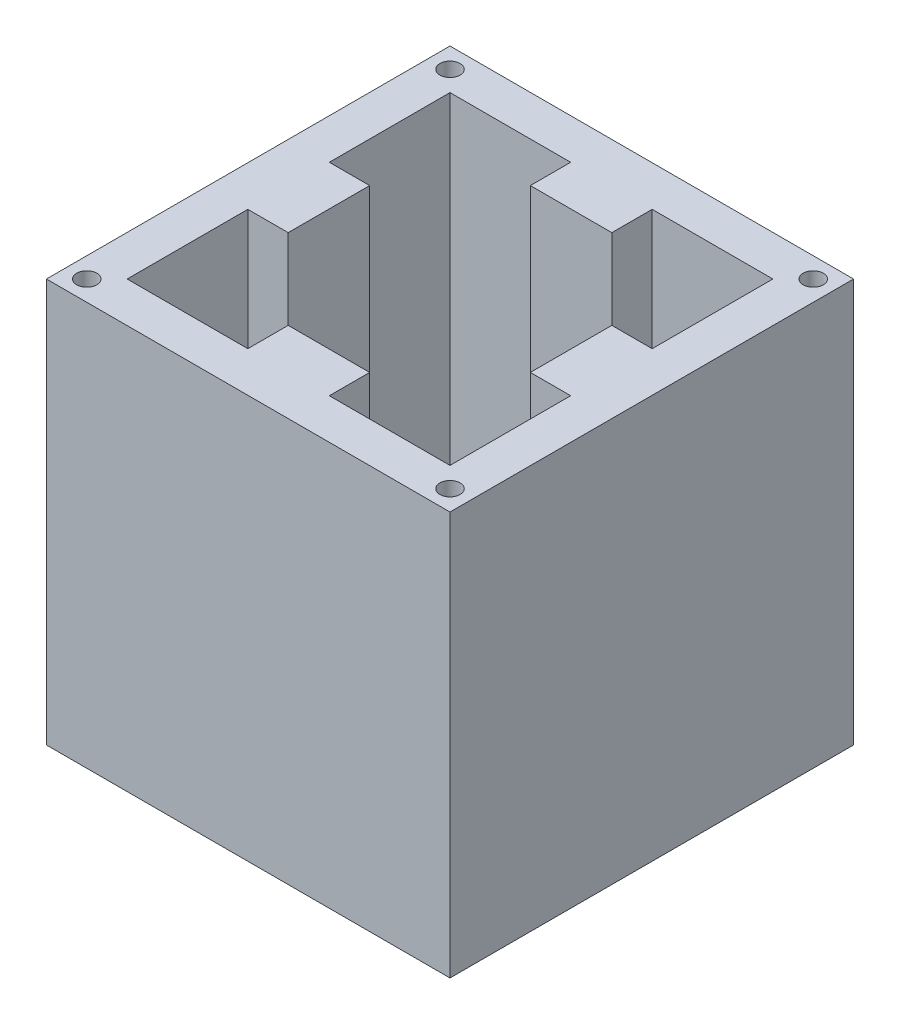
SolidWorks part; units mm, degrees
ref_plane "Front Plane" through (0, 0, 0) normal (0, 0, 1) x (1, 0, 0)
ref_plane "Top Plane" through (0, 0, 0) normal (0, 1, 0) x (1, 0, 0)
ref_plane "Right Plane" through (0, 0, 0) normal (1, 0, 0) x (0, 0, -1)
sketch "Sketch1" plane through (0, 0, 0) normal (0, 1, 0) x (1, 0, 0)
  line L1 (-12.7, -12.7) -> (12.7, -12.7)
  line L2 (-12.7, -12.7) -> (-12.7, 12.7)
  line L3 (-12.7, 12.7) -> (12.7, 12.7)
  line L4 (12.7, -12.7) -> (12.7, 12.7)
  line L5 (-12.7, -12.7) -> (12.7, 12.7) construction
  line L6 (-12.7, 12.7) -> (12.7, -12.7) construction
  point P0 (0, 0)
  dimension "D1" = 25.4
  dimension "D2" = 25.4
extrude "Boss-Extrude1" add sketch "Sketch1" along normal blind 25.4 contours L4 L1 L2 L3
sketch "Sketch3" plane through (0, 25.4, 0) normal (0, 1, 0) x (1, 0, 0)
  line L6 (10.16, 2.5651) -> (7.62, 2.5651)
  line L7 (7.62, 2.5651) -> (7.62, -2.5651)
  line L8 (7.62, -2.5651) -> (10.16, -2.5651)
  line L9 (10.16, 10.16) -> (-10.16, 10.16)
  line L10 (-10.16, 10.16) -> (-10.16, -10.16)
  line L11 (-10.16, -10.16) -> (10.16, -10.16)
  line L12 (10.16, -10.16) -> (10.16, 10.16)
  line L13 (10.16, 10.16) -> (2.5651, 10.16)
  line L14 (-10.16, 10.16) -> (-10.16, 2.5651)
  line L15 (-10.16, -10.16) -> (-2.5651, -10.16)
  line L16 (10.16, -10.16) -> (10.16, -2.5651)
  line L17 (-2.5651, -7.62) -> (-2.5651, -10.16)
  line L19 (2.5651, -10.16) -> (2.5651, -7.62)
  line L20 (2.5651, -7.62) -> (-2.5651, -7.62)
  line L21 (-7.62, 2.5651) -> (-10.16, 2.5651)
  line L23 (-10.16, -2.5651) -> (-7.62, -2.5651)
  line L24 (-7.62, -2.5651) -> (-7.62, 2.5651)
  line L25 (2.5651, 7.62) -> (2.5651, 10.16)
  line L27 (-2.5651, 10.16) -> (-2.5651, 7.62)
  line L28 (-2.5651, 7.62) -> (2.5651, 7.62)
  line L31 (-2.5651, 10.16) -> (-10.16, 10.16)
  line L33 (10.16, 2.5651) -> (10.16, 10.16)
  line L34 (2.5651, -10.16) -> (10.16, -10.16)
  line L35 (-10.16, -2.5651) -> (-10.16, -10.16)
  line L41 (-12.7, -12.7) -> (12.7, 12.7) construction
  line L42 (-12.7, 12.7) -> (12.7, -12.7) construction
  point P0 (0, 0)
  point P24 (0, 0)
  dimension "D2" = 5.1302
  dimension "D3" = 2.54
  dimension "D1" = 2.54
  dimension "D4" = 4
extrude "Cut-Extrude2" cut sketch "Sketch3" against normal blind 22.86
sketch "Sketch4" plane through (0, 25.4, 0) normal (0, 1, 0) x (1, 0, 0)
  line L0 (-12.7, 12.7) -> (12.7, -12.7) construction
  line L5 (-12.7, -12.7) -> (12.7, 12.7) construction
  line L6 (12.7, -12.7) -> (12.7, 12.7) construction
  circle A0 centre (11.43, 11.43) radius 0.635
  circle A4 centre (11.43, -11.43) radius 0.635
  circle A5 centre (-11.43, -11.43) radius 0.635
  circle A6 centre (-11.43, 11.43) radius 0.635
  point P15 (0, 0)
  point P19 (0, 0)
  dimension "D3" = 1.27
  dimension "D1" = 1.27
  dimension "D2" = 4
extrude "Cut-Extrude4" cut sketch "Sketch4" against normal blind 7.62
sketch "Sketch5" plane through (0, 2.54, 0) normal (0, 1, 0) x (1, 0, 0)
  circle A0 centre (0, 0) radius 4.1275
  dimension "D1" = 8.255
extrude "Boss-Extrude2" add sketch "Sketch5" along normal blind 7.62
chamfer "Chamfer1" distance 1.27 1 edges at (0, 10.16, 4.1275)
